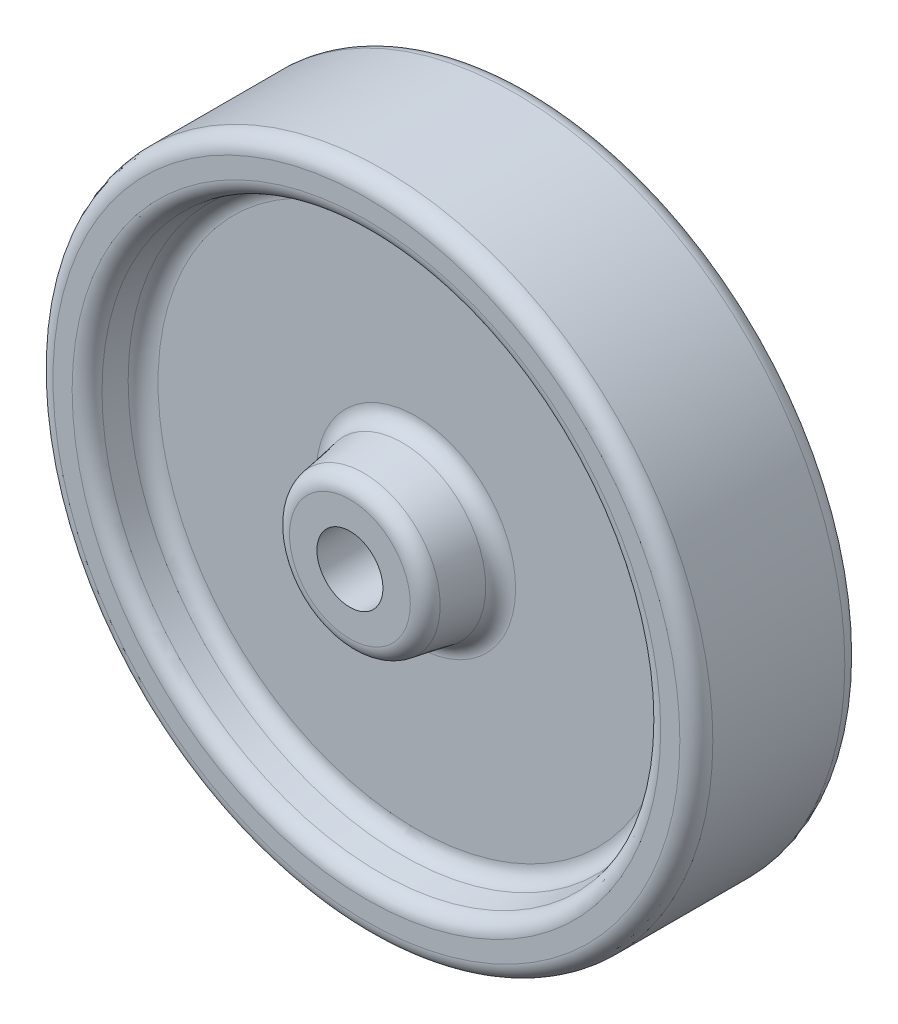
SolidWorks part; units mm, degrees
ref_plane "Piano frontale" through (0, 0, 0) normal (0, 0, 1) x (1, 0, 0)
ref_plane "Piano superiore" through (0, 0, 0) normal (0, 1, 0) x (1, 0, 0)
ref_plane "Piano destro" through (0, 0, 0) normal (1, 0, 0) x (0, 0, -1)
sketch "Schizzo1" plane through (0, 0, 0) normal (1, 0, 0) x (0, 0, -1)
  line L0 (0, 0) -> (71.4537, 0) construction
  line L1 (0, 0) -> (0, 105.6967) construction
  line L2 (-20, 100) -> (20, 100)
  line L3 (-30, 12.5) -> (30, 12.5)
  line L4 (30, 12.5) -> (30, 18.3045)
  line L5 (25, 95) -> (25, 89.1955)
  line L6 (20.8682, 84.2715) -> (14.1318, 83.0836)
  line L7 (10, 78.1596) -> (10, 30.222)
  line L8 (25.8682, 23.2285) -> (14.1318, 25.298)
  line L9 (-25.8682, 23.2285) -> (-14.1318, 25.298)
  line L10 (-10, 78.1596) -> (-10, 30.222)
  line L11 (-20.8682, 84.2715) -> (-14.1318, 83.0836)
  line L12 (-25, 95) -> (-25, 89.1955)
  line L13 (-30, 12.5) -> (-30, 18.3045)
  arc A0 (20, 100) -> (25, 95) centre (20, 95) cw
  arc A1 (25, 89.1955) -> (20.8682, 84.2715) centre (20, 89.1955) cw
  arc A2 (14.1318, 83.0836) -> (10, 78.1596) centre (15, 78.1596) ccw
  arc A3 (14.1318, 25.298) -> (10, 30.222) centre (15, 30.222) cw
  arc A4 (30, 18.3045) -> (25.8682, 23.2285) centre (25, 18.3045) ccw
  arc A5 (-30, 18.3045) -> (-25.8682, 23.2285) centre (-25, 18.3045) cw
  arc A6 (-14.1318, 25.298) -> (-10, 30.222) centre (-15, 30.222) ccw
  arc A7 (-14.1318, 83.0836) -> (-10, 78.1596) centre (-15, 78.1596) cw
  arc A8 (-25, 89.1955) -> (-20.8682, 84.2715) centre (-20, 89.1955) ccw
  arc A9 (-20, 100) -> (-25, 95) centre (-20, 95) ccw
  point P14 (25, 100)
  point P17 (25, 85)
  point P24 (30, 22.5)
  point P26 (0, 100)
  point P27 (0, 12.5)
  point P41 (-30, 22.5)
  point P42 (-25, 85)
  point P43 (-25, 100)
  dimension "D10" = 5
  dimension "D1" = 100
  dimension "D2" = 25
  dimension "D3" = 12.5
  dimension "D4" = 30
  dimension "D5" = 10
  dimension "D6" = 15
  dimension "D7" = 100
  dimension "D8" = 20
  dimension "D9" = 100
revolve "Rivoluzione1" add sketch "Schizzo1" angle 360 about L0
sketch "Schizzo2" plane through (0, 0, -30) normal (0, 0, -1) x (-1, 0, 0)
  circle A0 centre (0, 0) radius 10
  circle A1 centre (0, 0) radius 12.5
extrude "Estrusione1" add sketch "Schizzo2" against normal up to surface (60 mm away) up to face at (12.5, 0, 30)
